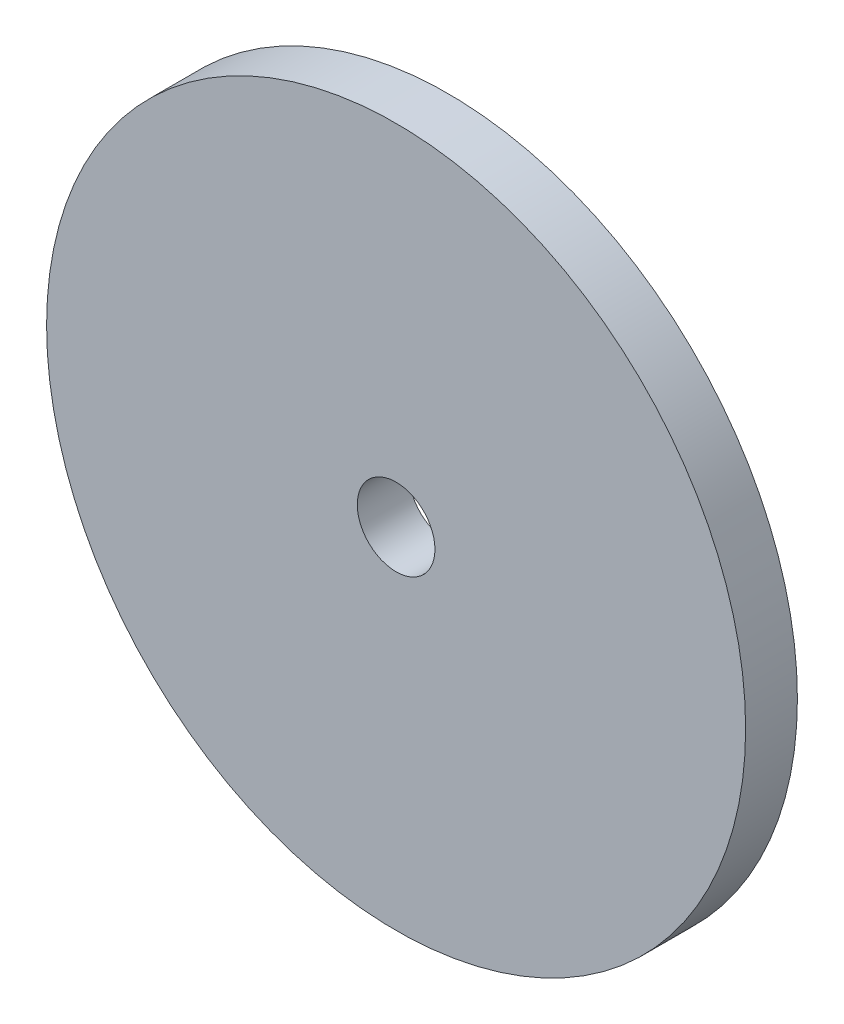
SolidWorks part; units mm, degrees
ref_plane "Front Plane" through (0, 0, 0) normal (0, 0, 1) x (1, 0, 0)
ref_plane "Top Plane" through (0, 0, 0) normal (0, 1, 0) x (1, 0, 0)
ref_plane "Right Plane" through (0, 0, 0) normal (1, 0, 0) x (0, 0, -1)
sketch "Sketch1" plane through (0, 0, 0) normal (0, 0, 1) x (1, 0, 0)
  circle A0 centre (0, 0) radius 13.5
  circle A1 centre (0, 0) radius 1.5
  dimension "D1" = 27
  dimension "D2" = 3
extrude "Boss-Extrude1" add sketch "Sketch1" along normal blind 2
